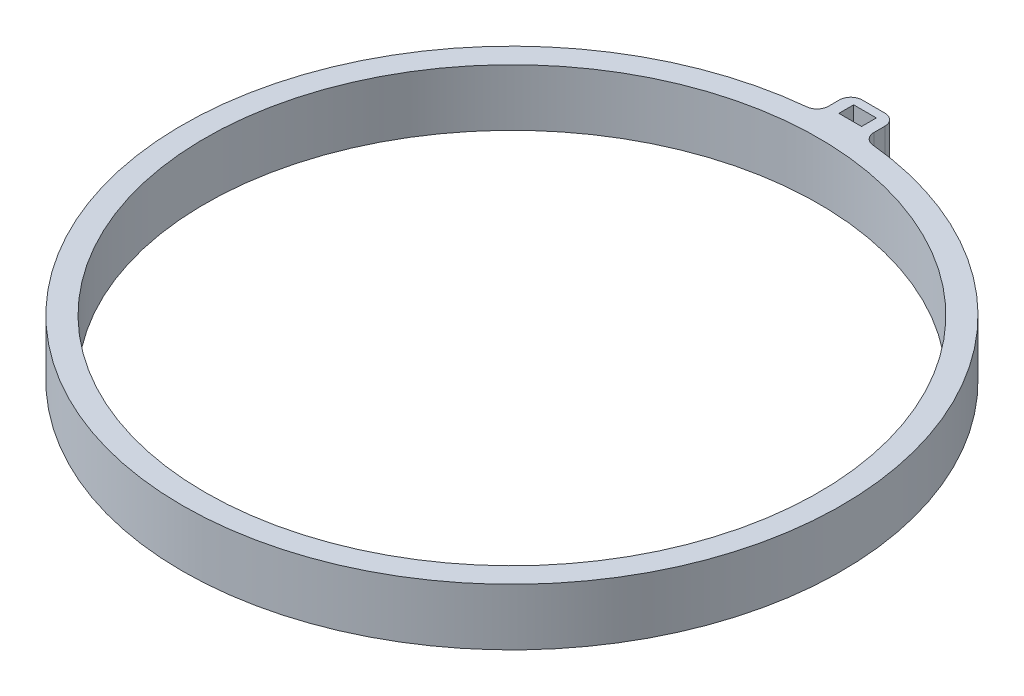
SolidWorks part; units mm, degrees
material "Nylon 101"
ref_plane "Plano frontal" through (0, 0, 0) normal (0, 0, 1) x (1, 0, 0)
ref_plane "Plano superior" through (0, 0, 0) normal (0, 1, 0) x (1, 0, 0)
ref_plane "Plano direito" through (0, 0, 0) normal (1, 0, 0) x (0, 0, -1)
sketch "Esboço1" plane through (0, 0, 0) normal (0, 1, 0) x (1, 0, 0)
  circle A0 centre (0, 0) radius 27
  circle A1 centre (0, 0) radius 29
  dimension "D1" = 54
  dimension "D2" = 2
extrude "Ressalto-extrusão1" add sketch "Esboço1" along normal blind 5
sketch "Esboço2" plane through (0, 5, 0) normal (0, 1, 0) x (1, 0, 0)
  line L0 (0, 21.6655) -> (0, 33.5896) construction
  line L2 (-2, 31.8145) -> (2, 31.8145)
  line L3 (-2, 31.8145) -> (-2, 27.8145)
  line L4 (-2, 27.8145) -> (2, 27.8145)
  line L5 (2, 31.8145) -> (2, 27.8145)
  line L6 (-2, 31.8145) -> (2, 27.8145) construction
  line L7 (-2, 27.8145) -> (2, 31.8145) construction
  point P3 (0, 29.8145)
  dimension "D1" = 4
  dimension "D2" = 4
extrude "Ressalto-extrusão2" add sketch "Esboço2" against normal through all
fillet "Filete1" radius 1 4 edges at (2, 2.5, -28.931) (-2, 2.5, -28.931) (2, 2.5, -31.8145) (-2, 2.5, -31.8145)
sketch "Esboço3" plane through (0, 0, 0) normal (0, -1, 0) x (1, 0, 0)
  line L1 (-1, -31.0686) -> (1, -31.0686)
  line L2 (-1, -31.0686) -> (-1, -29.7662)
  line L3 (-1, -29.7662) -> (1, -29.7662)
  line L4 (1, -31.0686) -> (1, -29.7662)
  line L5 (-1, -31.0686) -> (1, -29.7662) construction
  line L6 (-1, -29.7662) -> (1, -31.0686) construction
  point P0 (0, -30.4174)
extrude "Corte-extrusão1" cut sketch "Esboço3" against normal through all
